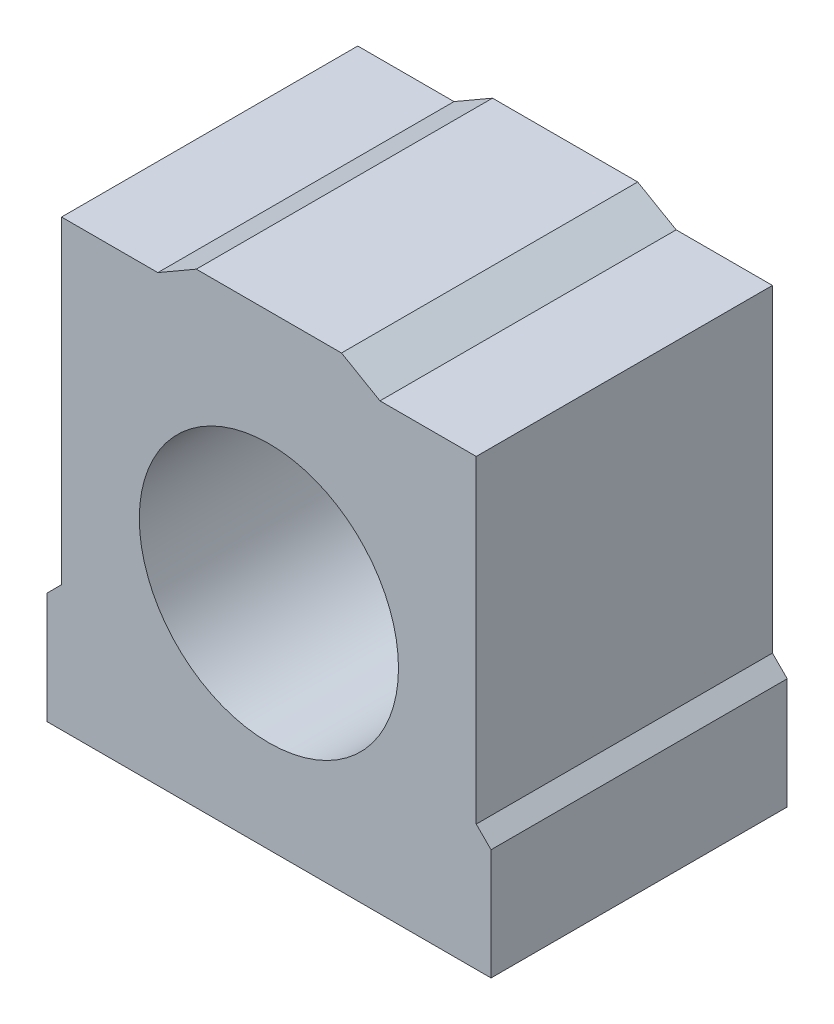
SolidWorks part; units mm, degrees
ref_plane "Alzado" through (0, 0, 0) normal (0, 0, 1) x (1, 0, 0)
ref_plane "Planta" through (0, 0, 0) normal (0, 1, 0) x (1, 0, 0)
ref_plane "Vista lateral" through (0, 0, 0) normal (1, 0, 0) x (0, 0, -1)
sketch "Croquis1" plane through (0, 0, 0) normal (0, 0, 1) x (1, 0, 0)
  line L0 (0, 0) -> (0, 50000) construction
  line L1 (28, 60) -> (15, 60)
  line L2 (30, 15) -> (30, 0)
  line L3 (30, 0) -> (-30, 0)
  line L4 (-30, 15) -> (-30, 0)
  line L7 (-28, 17) -> (-28, 60)
  line L8 (28, 17) -> (28, 60)
  line L9 (-15, 60) -> (-9.8038, 63)
  line L10 (15, 60) -> (9.8038, 63)
  line L11 (-9.8038, 63) -> (9.8038, 63)
  line L12 (-28, 17) -> (-30, 15)
  line L13 (28, 17) -> (30, 15)
  line L14 (-15, 60) -> (-28, 60)
  circle A0 centre (0, 30) radius 17.5
  point P0 (0, 0)
  point P16 (0, 63)
  dimension "D9" = 35
  dimension "D3" = 135
  dimension "D4" = 150
  dimension "D5" = 28
  dimension "D6" = 3
  dimension "D7" = 15
  dimension "D8" = 15
  dimension "D1" = 60
  dimension "D2" = 60
  dimension "D10" = 30
extrude "Saliente-Extruir1" add sketch "Croquis1" along normal mid plane 40
hole_wizard "Taladro roscado 1/4-201" positions "Croquis2" profile "Croquis3" tap size "1/4-20" standard "Ansi Inch"
sketch "Croquis2" plane through (0, 0, 0) normal (0, -1, 0) x (-1, 0, 0)
  line L0 (0, 0) -> (0, -2994.4095) construction
  line L3 (30, 20) -> (-30, 20) construction
  line L4 (30, -20) -> (30, 20) construction
  line L6 (0, 0) -> (50000, 0) construction
  point P0 (20, 10)
  point P22 (20, -10)
  point P24 (-20, -10)
  point P25 (-20, 10)
  dimension "D1" = 10
  dimension "D2" = 10
sketch "Croquis3" plane through (-20, 0, -10) normal (1, 0, 0) x (0, 0, -1)
  line L0 (0, 0) -> (0, 20.5838)
  line L1 (0, 20.5838) -> (2.5527, 19.05)
  line L2 (2.5527, 19.05) -> (2.5527, 0)
  line L5 (2.5527, 0) -> (0, 0)
  line L10 (0, 20.5838) -> (-2.5527, 19.05) construction
  line L11 (0, -6.35) -> (0, 107.95) construction
  dimension "Diámetro de perforador para roscar" = 5.1054
  dimension "Profundidad de perforador para roscar" = 19.05
  dimension "Ángulo de perforador" = 118
equation "\"D5@Croquis1\"=\"D1@Croquis1\"/2-2"
